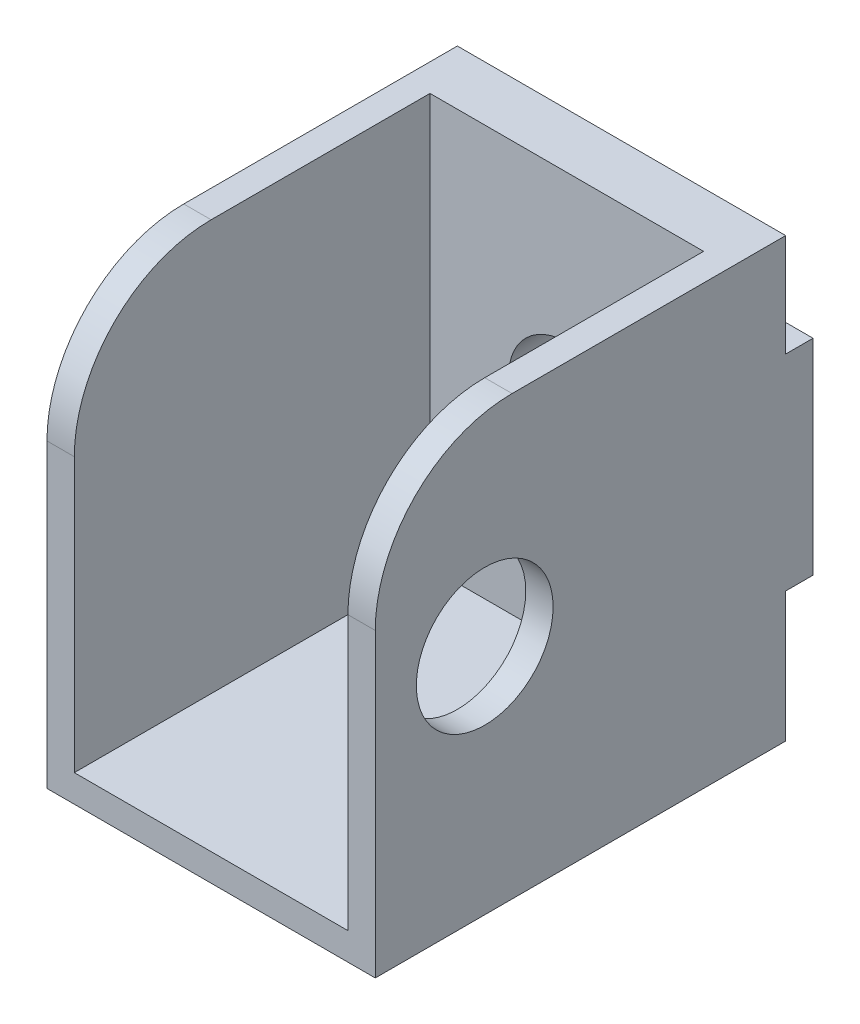
SolidWorks part; units mm, degrees
ref_plane "Front Plane" through (0, 0, 0) normal (0, 0, 1) x (1, 0, 0)
ref_plane "Top Plane" through (0, 0, 0) normal (0, 1, 0) x (1, 0, 0)
ref_plane "Right Plane" through (0, 0, 0) normal (1, 0, 0) x (0, 0, -1)
sketch "Sketch1" plane through (0, 0, 0) normal (0, 0, 1) x (1, 0, 0)
  line L1 (-10, -15) -> (10, -15)
  line L2 (-10, -15) -> (-10, 15)
  line L3 (-10, 15) -> (10, 15)
  line L4 (10, -15) -> (10, 15)
  line L5 (-10, -15) -> (10, 15) construction
  line L6 (-10, 15) -> (10, -15) construction
  circle A0 centre (0, 0) radius 4.25
  point P0 (0, 0)
  dimension "D3" = 8.5
  dimension "D1" = 20
  dimension "D2" = 30
extrude "Boss-Extrude1" add sketch "Sketch1" along normal blind 4
ref_plane "Plane1" through (0, -15, 0) normal (0, -1, 0) x (-1, 0, 0)
sketch "Sketch2" plane through (0, -15, 0) normal (0, -1, 0) x (-1, 0, 0)
  line L1 (-10, 0) -> (10, 0)
  line L2 (-10, 0) -> (-10, -30)
  line L3 (-10, -30) -> (10, -30)
  line L4 (10, 0) -> (10, -30)
  dimension "D1" = 20
  dimension "D2" = 30
extrude "Boss-Extrude2" add sketch "Sketch2" along normal blind 2
ref_plane "Plane2" through (-10, 0, 0) normal (-1, 0, 0) x (0, 0, 1)
sketch "Sketch4" plane through (-10, 0, 0) normal (-1, 0, 0) x (0, 0, 1)
  line L1 (0, 15) -> (20, 15)
  line L2 (0, 15) -> (0, -17)
  line L3 (0, -17) -> (30, -17)
  line L4 (30, 5) -> (30, -17)
  arc A0 (30, 5) -> (20, 15) centre (20, 5) ccw
  dimension "D1" = 10
extrude "Boss-Extrude3" add sketch "Sketch4" along normal blind 2
ref_plane "Plane3" through (10, 0, 0) normal (1, 0, 0) x (0, 0, -1)
sketch "Sketch5" plane through (10, 0, 0) normal (1, 0, 0) x (0, 0, -1)
  line L1 (0, 15) -> (-20, 15)
  line L2 (0, 15) -> (0, -17)
  line L3 (0, -17) -> (-30, -17)
  line L4 (-30, 5) -> (-30, -17)
  circle A0 centre (-22, 0) radius 5
  arc A1 (-30, 5) -> (-20, 15) centre (-20, 5) cw
  dimension "D1" = 10
  dimension "D4" = 10
  dimension "D2" = 8
  dimension "D3" = 15
extrude "Boss-Extrude4" add sketch "Sketch5" along normal blind 2
sketch "Sketch6" plane through (0, 0, 0) normal (0, 0, -1) x (-1, 0, 0)
  line L0 (-10, 16.5) -> (-10, -16.5) construction
  line L1 (-10, -7.5) -> (-12, -7.5)
  line L2 (-10, -7.5) -> (-10, 7.5)
  line L3 (-10, 7.5) -> (-12, 7.5)
  line L4 (-12, -7.5) -> (-12, 7.5)
  line L5 (-12, -17) -> (-12, 15) construction
  line L6 (0, 16.5) -> (0, -16.5) construction
  line L7 (10, 7.5) -> (12, 7.5)
  line L8 (12, -7.5) -> (12, 7.5)
  line L9 (10, -7.5) -> (12, -7.5)
  line L10 (10, -7.5) -> (10, 7.5)
  dimension "D1" = 15
  dimension "D2" = 7.5
extrude "Boss-Extrude5" add sketch "Sketch6" along normal blind 2
